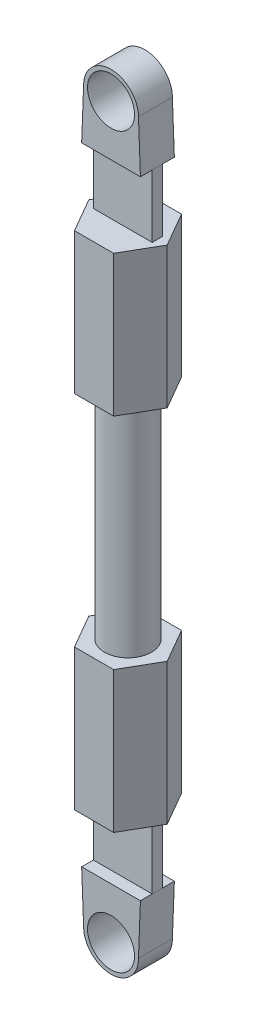
SolidWorks part; units mm, degrees
ref_plane "Front Plane" through (0, 0, 0) normal (0, 0, 1) x (1, 0, 0)
ref_plane "Top Plane" through (0, 0, 0) normal (0, 1, 0) x (1, 0, 0)
ref_plane "Right Plane" through (0, 0, 0) normal (1, 0, 0) x (0, 0, -1)
sketch "Sketch1" plane through (0, 0, 0) normal (0, 1, 0) x (1, 0, 0)
  line L1 (2.5, 0) -> (1.25, 2.1651)
  line L2 (1.25, 2.1651) -> (-1.25, 2.1651)
  line L3 (-1.25, 2.1651) -> (-2.5, 0)
  line L4 (-2.5, 0) -> (-1.25, -2.1651)
  line L5 (-1.25, -2.1651) -> (1.25, -2.1651)
  line L6 (1.25, -2.1651) -> (2.5, 0)
  circle A0 centre (0, 0) radius 2.1651 construction
  dimension "D1" = 5
extrude "Boss-Extrude1" add sketch "Sketch1" along normal blind 9
sketch "Sketch2" plane through (0, 0, 0) normal (0, -1, 0) x (1, 0, 0)
  circle A0 centre (0, 0) radius 1.5
  dimension "D1" = 3
extrude "Boss-Extrude2" add sketch "Sketch2" along normal blind 7
sketch "Sketch3" plane through (0, 9, 0) normal (0, 1, 0) x (1, 0, 0)
  line L0 (-1.25, 2.1651) -> (-2.5, 0) construction
  line L1 (-1.875, 1.0825) -> (1.875, 1.0825)
  line L2 (-1.875, 1.0825) -> (-1.875, -1.0825)
  line L3 (-1.875, -1.0825) -> (1.875, -1.0825)
  line L4 (1.875, 1.0825) -> (1.875, -1.0825)
  line L5 (1.25, -2.1651) -> (2.5, 0) construction
extrude "Boss-Extrude3" add sketch "Sketch3" along normal blind 9
sketch "Sketch4" plane through (-1.875, 0, 0) normal (-1, 0, 0) x (0, 0, 1)
  line L0 (-1.0825, 18) -> (-1.0825, 9) construction
  line L1 (-1.0825, 13) -> (-0.3325, 13)
  line L2 (-1.0825, 13) -> (-1.0825, 9)
  line L3 (-1.0825, 9) -> (-0.3325, 9)
  line L4 (1.0825, 13) -> (1.0825, 9)
  line L5 (-0.3325, 13) -> (-0.3325, 9)
  line L6 (0.3325, 13) -> (0.3325, 9)
  line L7 (0.3325, 13) -> (1.0825, 13)
  line L8 (0.3325, 9) -> (1.0825, 9)
  dimension "D1" = 4
  dimension "D2" = 0.75
  dimension "D3" = 0.75
extrude "Cut-Extrude1" cut sketch "Sketch4" against normal through all
sketch "Sketch5" plane through (0, 0, -1.0825) normal (0, 0, -1) x (-1, 0, 0)
  line L0 (-1.875, 18) -> (1.875, 18) construction
  line L1 (1.75, 16.25) -> (1.875, 13)
  line L2 (-1.75, 16.25) -> (-1.875, 13)
  line L3 (-1.875, 13) -> (-1.875, 18)
  line L4 (-1.875, 18) -> (1.875, 18)
  line L5 (1.875, 18) -> (1.875, 13)
  arc A0 (1.75, 16.25) -> (-1.75, 16.25) centre (0, 16.25) ccw
  circle A1 centre (0, 16.25) radius 1.5
  line M2 (-1.875, 18) -> (-1.875, 13)
  line M4 (1.875, 13) -> (1.875, 18)
  line M5 (1.875, 18) -> (-1.875, 18)
  dimension "D2" = 3.5
  dimension "D1" = 3
extrude "Cut-Extrude2" cut sketch "Sketch5" against normal through all contours A1 | A0 L4 L2 M2 | A0 L1 M4 M5
mirror "Mirror1" about plane through (0, -7, 0) normal (0, -1, 0) of bodies 105
